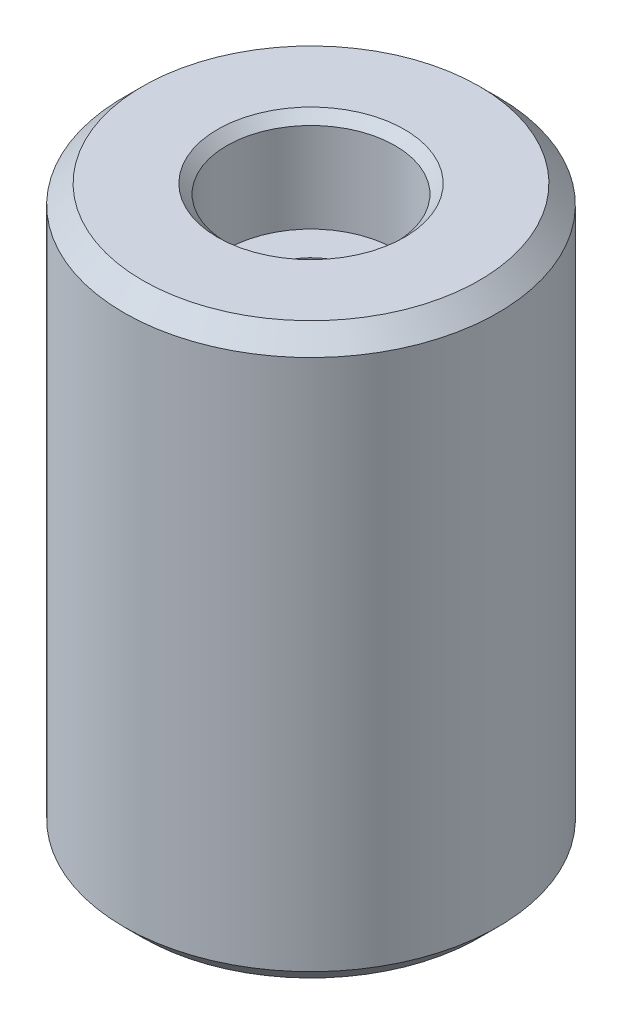
SolidWorks part; units mm, degrees
material "Plain Carbon Steel"
ref_plane "Front Plane" through (0, 0, 0) normal (0, 0, 1) x (1, 0, 0)
ref_plane "Top Plane" through (0, 0, 0) normal (0, 1, 0) x (1, 0, 0)
ref_plane "Right Plane" through (0, 0, 0) normal (1, 0, 0) x (0, 0, -1)
sketch "Sketch1" plane through (0, 0, 0) normal (0, 1, 0) x (1, 0, 0)
  circle A0 centre (0, 0) radius 20
  dimension "D1" = 40
extrude "Boss-Extrude1" add sketch "Sketch1" against normal blind 60.9
hole_wizard "CBORE for M10 Hex Socket Head Cap Screw1" positions "Sketch5" profile "Sketch3" counterbore size "M10" standard "ISO" end condition through all
sketch "Sketch5" plane through (0, 0, 0) normal (0, 1, 0) x (1, 0, 0)
  point P0 (0, 0)
sketch "Sketch3" plane through (0, 0, 0) normal (1, 0, 0) x (0, 0, 1)
  line L0 (0, 0) -> (0, 60.9)
  line L1 (0, 60.9) -> (5.25, 60.9)
  line L3 (5.25, 60.9) -> (5.25, 10.6)
  line L4 (5.25, 10.6) -> (9, 10.6)
  line L5 (9, 10.6) -> (9, 0)
  line L7 (9, 0) -> (0, 0)
  line L11 (0, -6.35) -> (0, 107.95) construction
  dimension "Thru Hole Dia." = 10.5
  dimension "Thru Hole Depth" = 60.9
  dimension "C'Bore Dia." = 18
  dimension "C'Bore Depth" = 10.6
chamfer "Chamfer1" distance 2 angle 45 2 edges at (0, -60.9, 20) (0, 0, 20)
chamfer "Chamfer2" distance 1 angle 45 1 edges at (0, 0, 9)
chamfer "Chamfer3" distance 1 angle 45 1 edges at (0, -60.9, 5.25)
